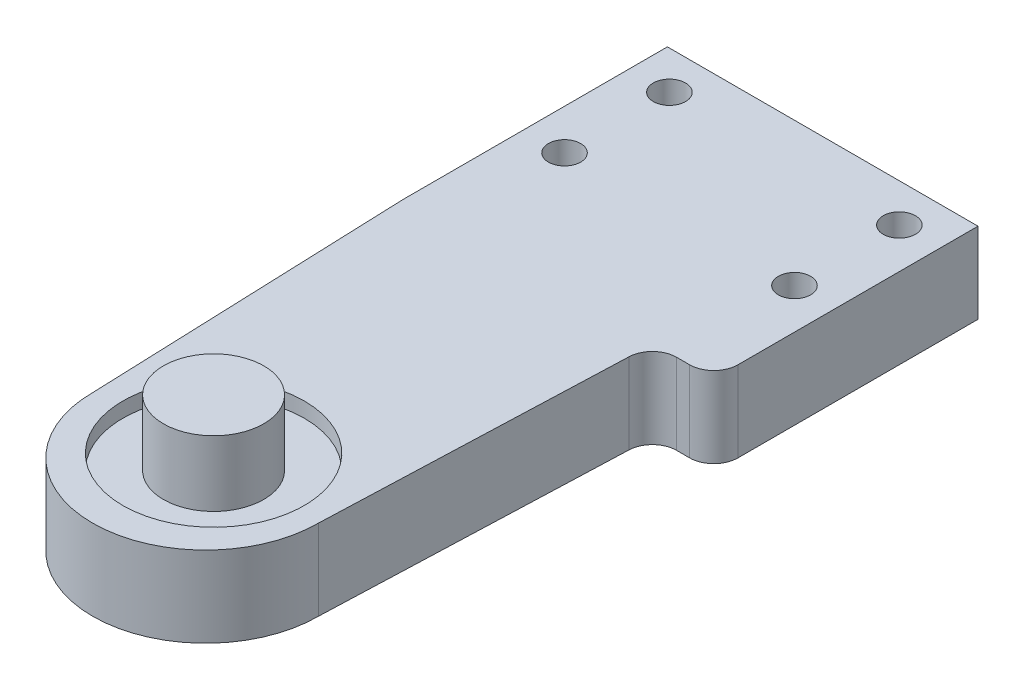
SolidWorks part; units mm, degrees
ref_plane "Front Plane" through (0, 0, 0) normal (0, 0, 1) x (1, 0, 0)
ref_plane "Top Plane" through (0, 0, 0) normal (0, 1, 0) x (1, 0, 0)
ref_plane "Right Plane" through (0, 0, 0) normal (1, 0, 0) x (0, 0, -1)
sketch "Sketch1" plane through (0, 0, 0) normal (0, 1, 0) x (1, 0, 0)
  line L0 (-19.25, 11.25) -> (19.25, 11.25)
  line L1 (-19.25, -11.5) -> (19.25, -11.5)
  line L2 (-19.25, -11.5) -> (-19.25, 11.5)
  line L3 (-19.25, 11.5) -> (19.25, 11.5)
  line L4 (19.25, -11.5) -> (19.25, 11.5)
  line L5 (-19.25, -11.5) -> (19.25, 11.5) construction
  line L6 (-19.25, 11.5) -> (19.25, -11.5) construction
  point P0 (0, 0)
  dimension "D1" = 38.5
  dimension "D2" = 23
  dimension "D3" = 0.25
extrude "Boss-Extrude1" add sketch "Sketch1" along normal blind 10 contours L1 L4 L0 L2
sketch "Sketch2" plane through (0, 10, 0) normal (0, 1, 0) x (1, 0, 0)
  line L1 (-14.25, -6.5) -> (14.25, -6.5) construction
  line L2 (-14.25, -6.5) -> (-14.25, 6.5) construction
  line L3 (-14.25, 6.5) -> (14.25, 6.5) construction
  line L4 (14.25, -6.5) -> (14.25, 6.5) construction
  line L5 (-14.25, -6.5) -> (14.25, 6.5) construction
  line L6 (-14.25, 6.5) -> (14.25, -6.5) construction
  point P1 (14.25, 6.5)
  point P2 (-14.25, -6.5)
  point P3 (-14.25, 6.5)
  point P4 (14.25, -6.5)
  point P11 (-14.25, 6.5)
  point P13 (-14.25, -6.5)
  point P17 (14.25, 6.5)
  point P22 (14.25, 6.5)
  point P23 (0, 0)
  dimension "D1" = 28.5
  dimension "D2" = 13
hole_wizard "Ø4.0mm Dowel Hole1" positions "Sketch2" profile "Sketch3" hole size "Ø4.0" standard "ANSI Metric" end condition through all
sketch "Sketch3" plane through (14.25, 10, -6.5) normal (1, 0, 0) x (0, 0, 1)
  line L0 (0, 0) -> (0, 10)
  line L1 (0, 10) -> (2, 10)
  line L2 (2, 10) -> (2, 0)
  line L5 (2, 0) -> (0, 0)
  line L11 (0, -6.35) -> (0, 107.95) construction
  dimension "Thru Hole Dia." = 4
  dimension "Thru Hole Depth" = 10
sketch "Sketch4" plane through (0, 10, 0) normal (0, -1, 0) x (1, 0, 0)
  line L10 (-19.25, 11.5) -> (19.25, 11.5)
  line L11 (19.25, 11.5) -> (19.25, 18.5)
  line L12 (16.25, 21.5) -> (14.6396, 21.5)
  line L13 (11.6417, 24.3876) -> (10.25, 61.5)
  line L14 (3.5, 73.4765) -> (3.5, 60.5)
  line L15 (3.5, 60.5) -> (1.5, 29.5)
  line L16 (-9, 29.5) -> (-11, 60.5)
  line L17 (-11, 60.5) -> (-11, 73.4765)
  line L18 (-17.75, 61.5) -> (-19.25, 21.5)
  line L19 (-19.25, 21.5) -> (-19.25, 11.5)
  line L20 (-19.25, 11.5) -> (19.25, 11.5)
  line L21 (19.25, 11.5) -> (19.25, 18.5)
  line L22 (16.25, 21.5) -> (14.6396, 21.5)
  line L23 (11.6417, 24.3876) -> (10.25, 61.5)
  line L24 (3.5, 73.4765) -> (3.5, 60.5) construction
  line L25 (3.5, 60.5) -> (1.5, 29.5) construction
  line L26 (-9, 29.5) -> (-11, 60.5) construction
  line L27 (-11, 60.5) -> (-11, 73.4765) construction
  line L28 (-17.75, 61.5) -> (-19.25, 21.5)
  line L29 (-19.25, 21.5) -> (-19.25, 11.5)
  circle A0 centre (-3.75, 60.5) radius 3.25 construction
  circle A1 centre (-3.75, 60.5) radius 3.25 construction
  arc A5 (19.25, 18.5) -> (16.25, 21.5) centre (16.25, 18.5) ccw
  arc A6 (11.6417, 24.3876) -> (14.6396, 21.5) centre (14.6396, 24.5) ccw
  arc A7 (10.25, 61.5) -> (3.5, 73.4765) centre (-3.75, 61.5) ccw
  arc A8 (-9, 29.5) -> (1.5, 29.5) centre (-3.75, 29.5) ccw
  arc A9 (-11, 73.4765) -> (-17.75, 61.5) centre (-3.75, 61.5) ccw
  arc A10 (19.25, 18.5) -> (16.25, 21.5) centre (16.25, 18.5) ccw
  arc A11 (11.6417, 24.3876) -> (14.6396, 21.5) centre (14.6396, 24.5) ccw
  arc A12 (10.25, 61.5) -> (3.5, 73.4765) centre (-3.75, 61.5) ccw
  arc A13 (-9, 29.5) -> (1.5, 29.5) centre (-3.75, 29.5) ccw construction
  arc A14 (-11, 73.4765) -> (-17.75, 61.5) centre (-3.75, 61.5) ccw
  arc A22 (10.25, 61.5) -> (-17.75, 61.5) centre (-3.75, 61.5) ccw
  dimension "D1" = 0
extrude "Boss-Extrude2" add sketch "Sketch4" along normal up to surface (10 mm away) up to face at (14.25, 0, 8.5)
sketch "Sketch5" plane through (0, 10, 0) normal (0, 1, 0) x (1, 0, 0)
  circle A0 centre (-3.75, -60.5) radius 3.25 construction
  circle A1 centre (-3.75, -60.5) radius 3.25 construction
  circle A2 centre (-3.75, -60.5) radius 11.2395
  dimension "D1" = 22.479
extrude "Cut-Extrude1" cut sketch "Sketch5" against normal blind 1.8542
sketch "Sketch6" plane through (0, 8.1458, 0) normal (0, 1, 0) x (1, 0, 0)
  circle A2 centre (-3.75, -60.5) radius 6.223
  circle A3 centre (-3.75, -60.5) radius 11.2395 construction
  circle A4 centre (-3.75, -60.5) radius 11.2395 construction
  dimension "D1" = 12.446
extrude "Boss-Extrude3" add sketch "Sketch6" along normal blind 8.128
